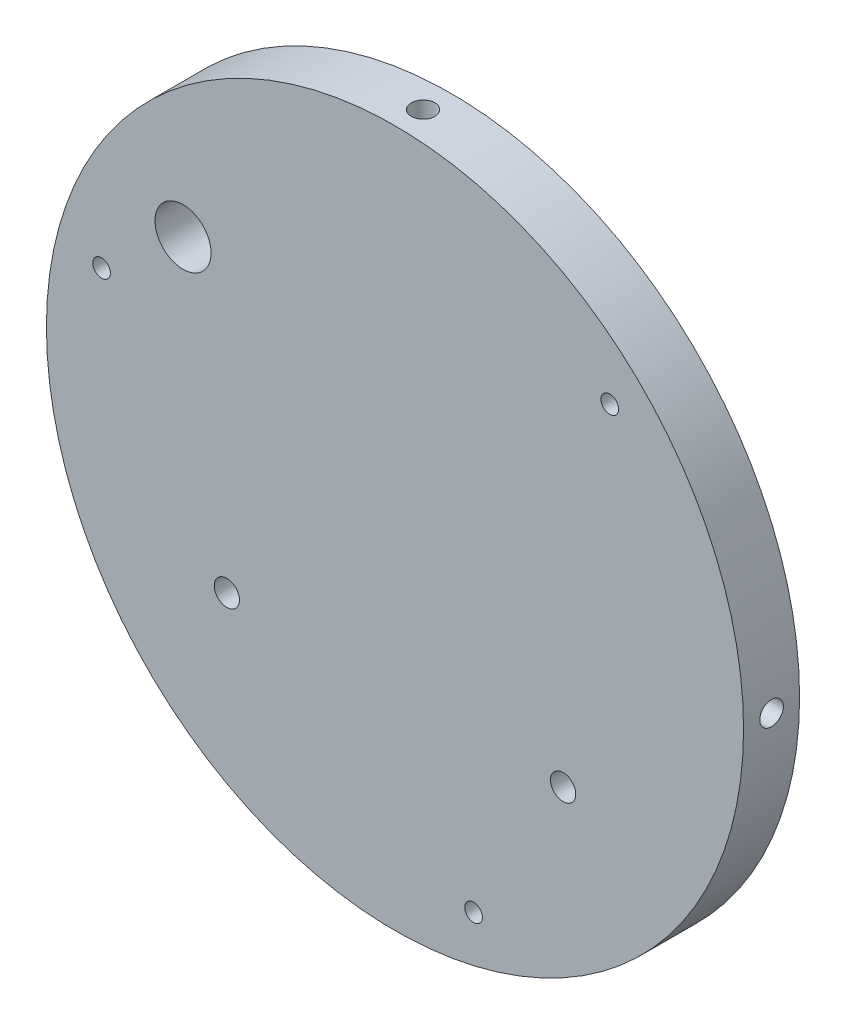
SolidWorks part; units mm, degrees
ref_plane "Ön Düzlem" through (0, 0, 0) normal (0, 0, 1) x (1, 0, 0)
ref_plane "Üst Düzlem" through (0, 0, 0) normal (0, 1, 0) x (1, 0, 0)
ref_plane "Sağ Düzlem" through (0, 0, 0) normal (1, 0, 0) x (0, 0, -1)
sketch "Çizim1" plane through (0, 0, 0) normal (0, 0, 1) x (1, 0, 0)
  circle A0 centre (0, 0) radius 62.2
  dimension "D1" = 124.4
extrude "Yükseklik-Ekstrüzyon1" add sketch "Çizim1" along normal blind 10
sketch "Çizim2" plane through (0, 0, 10) normal (0, 0, 1) x (1, 0, 0)
  line L0 (0, 0) -> (0, 26.5815) construction
  line L1 (0, 0) -> (38.3252, 38.3252) construction
  circle A0 centre (0, 0) radius 54.2 construction
  point P4 (38.3252, 38.3252)
  point P9 (38.3252, 38.3252)
  dimension "D2" = 108.4
  dimension "D1" = 45
hole_wizard "M3x0.5 Helisarmal İçin Dişli Delik2" positions "Çizim2" profile "Çizim4" tap size "M3x0.5" standard "Helicoil® Metric" end condition through all
sketch "Çizim4" plane through (38.3252, 38.3252, 10) normal (1, 0, 0) x (0, -1, 0)
  line L0 (0, 0) -> (0, 10)
  line L1 (0, 10) -> (1.575, 10)
  line L2 (1.575, 10) -> (1.575, 0)
  line L5 (1.575, 0) -> (0, 0)
  line L11 (0, -6.35) -> (0, 107.95) construction
  dimension "Thru Tap Drill Dia." = 3.15
  dimension "Thru Tap Drill Depth" = 10
cosmetic thread "Delik Dişi1" parameters "D1"=3.5, "D2"=3.716
pattern_circular "Dairesel Kaplama1" count 3 over 360 about axis through (0, 0, 0) along (0, 0, 1) of "M3x0.5 Helisarmal İçin Dişli Delik2"
cosmetic thread "Delik Dişi2" parameters "D1"=3.5, "D2"=3.716
cosmetic thread "Delik Dişi3" parameters "D1"=3.5, "D2"=3.716
sketch "Çizim5" plane through (0, 0, 10) normal (0, 0, 1) x (1, 0, 0)
  line L0 (0, 0) -> (0, 25.8431) construction
  line L1 (0, 0) -> (-37.8186, 26.099) construction
  circle A0 centre (-37.8186, 26.099) radius 5
  dimension "D3" = 10
  dimension "D1" = 55.39
  dimension "D2" = 45.95
extrude "Kes-Ekstrüzyon1" cut sketch "Çizim5" against normal blind 10
sketch "Çizim6" plane through (0, 0, 10) normal (0, 0, 1) x (1, 0, 0)
  line L0 (0, 0) -> (0, -25) construction
  line L1 (30, -25) -> (-30, -25) construction
  circle A2 centre (30, -25) radius 2.25
  circle A3 centre (-30, -25) radius 2.25
  point P6 (0, -25)
  dimension "D2" = 60
  dimension "D3" = 4.5
  dimension "D4" = 4.5
  dimension "D1" = 25
extrude "Kes-Ekstrüzyon2" cut sketch "Çizim6" against normal blind 10
ref_plane "Düzlem1" through (0, 62.2, 0) normal (0, 1, 0) x (1, 0, 0)
sketch "Çizim9" plane through (0, 62.2, 0) normal (0, 1, 0) x (1, 0, 0)
  line L0 (0, 0) -> (0, -5) construction
  line L1 (62.2, 0) -> (-62.2, 0) construction
  point P1 (0, -5)
  point P9 (0, -5)
  dimension "D1" = 5
hole_wizard "M4x0.7 Helisarmal İçin Dişli Delik4" positions "Çizim9" profile "Çizim10" tap size "M4x0.7" standard "Helicoil® Metric"
sketch "Çizim10" plane through (0, 62.2, 5) normal (1, 0, 0) x (0, 0, 1)
  line L0 (0, 0) -> (0, 13.5618)
  line L1 (0, 13.5618) -> (2.1, 12.3)
  line L2 (2.1, 12.3) -> (2.1, 0)
  line L5 (2.1, 0) -> (0, 0)
  line L10 (0, 13.5618) -> (-2.1, 12.3) construction
  line L11 (0, -6.35) -> (0, 107.95) construction
  dimension "Tap Drill Dia." = 4.2
  dimension "Tap Drill Depth" = 12.3
  dimension "Drill Angle" = 118
pattern_circular "Dairesel Kaplama2" count 4 over 360 about axis through (0, 0, 0) along (0, 0, 1) of "M4x0.7 Helisarmal İçin Dişli Delik4"
